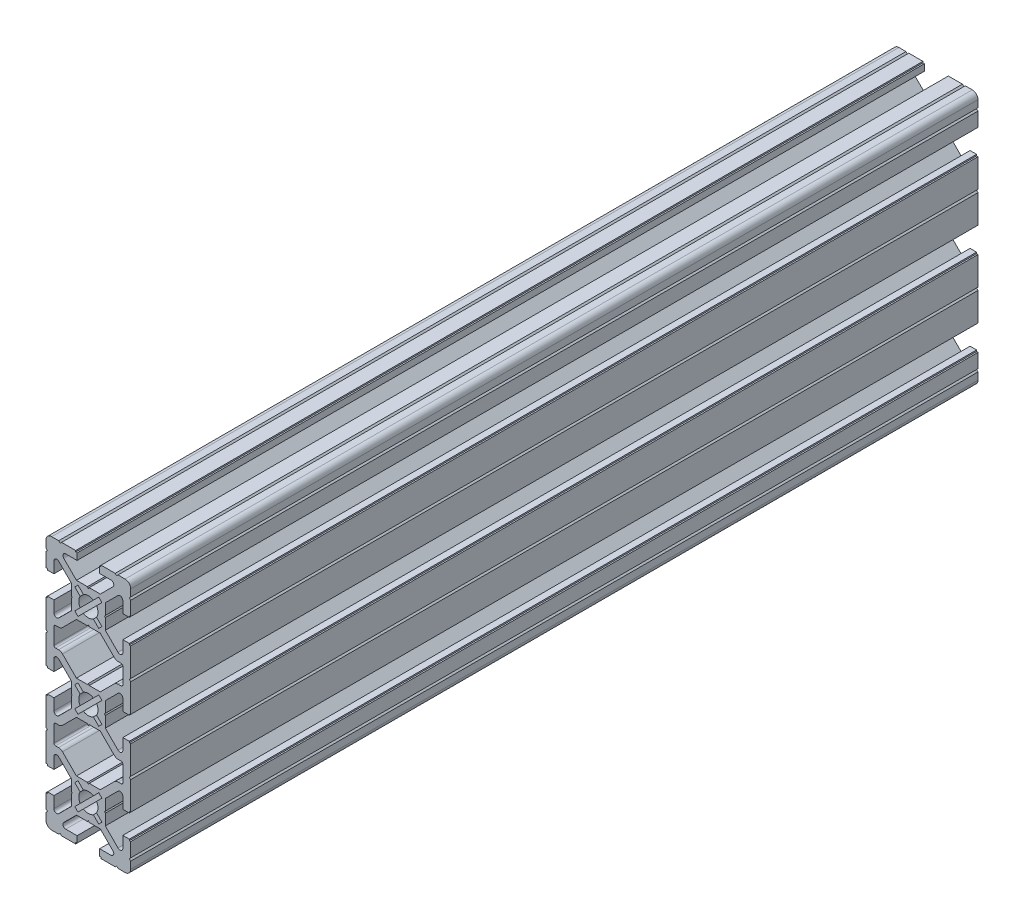
SolidWorks part; units mm, degrees
material "6063-T5"
ref_plane "Face" through (0, 0, 0) normal (0, 0, 1) x (1, 0, 0)
ref_plane "Dessus" through (0, 0, 0) normal (0, 1, 0) x (1, 0, 0)
ref_plane "Droite" through (0, 0, 0) normal (1, 0, 0) x (0, 0, -1)
other "Centre de masse"
sketch "Esquisse1" plane through (0, 0, 0) normal (0, 0, 1) x (1, 0, 0)
  line L0 (2.9023, -1.771) -> (4.8083, -3.677)
  line L1 (4.8083, -3.677) -> (3.677, -4.8083)
  line L2 (3.677, -4.8083) -> (1.771, -2.9023)
  line L3 (-1.771, -2.9023) -> (-3.677, -4.8083)
  line L4 (-3.677, -4.8083) -> (-4.8083, -3.677)
  line L5 (-4.8083, -3.677) -> (-2.9023, -1.771)
  line L6 (-2.9023, -28.229) -> (-4.8083, -26.323)
  line L7 (-4.8083, -26.323) -> (-3.677, -25.1917)
  line L8 (-3.677, -25.1917) -> (-1.771, -27.0977)
  line L9 (1.771, -27.0977) -> (3.677, -25.1917)
  line L10 (3.677, -25.1917) -> (4.8083, -26.323)
  line L11 (4.8083, -26.323) -> (2.9023, -28.229)
  line L12 (2.9023, -31.771) -> (4.8083, -33.677)
  line L13 (4.8083, -33.677) -> (3.677, -34.8083)
  line L14 (3.677, -34.8083) -> (1.771, -32.9023)
  line L15 (-1.771, -32.9023) -> (-3.677, -34.8083)
  line L16 (-3.677, -34.8083) -> (-4.8083, -33.677)
  line L17 (-4.8083, -33.677) -> (-2.9023, -31.771)
  line L18 (-9.1584, -10.9442) -> (-4.2142, -6)
  line L19 (-4.2142, -6) -> (-0.3125, -6)
  line L20 (-0.3125, -6) -> (0, -6.4691)
  line L21 (0, -6.4691) -> (0.3125, -6)
  line L22 (0.3125, -6) -> (4.2142, -6)
  line L23 (4.2142, -6) -> (9.1584, -10.9442)
  line L24 (10.5726, -11.53) -> (11.6, -11.53)
  line L25 (12.2, -12.13) -> (12.2, -17.87)
  line L26 (11.6, -18.47) -> (10.5726, -18.47)
  line L27 (9.1584, -19.0558) -> (4.2142, -24)
  line L28 (4.2142, -24) -> (0.3125, -24)
  line L29 (0.3125, -24) -> (0, -24.5)
  line L30 (0, -24.5) -> (-0.3125, -24)
  line L31 (-0.3125, -24) -> (-4.2142, -24)
  line L32 (-4.2142, -24) -> (-9.1584, -19.0558)
  line L33 (-10.5726, -18.47) -> (-11.6, -18.47)
  line L34 (-12.2, -17.87) -> (-12.2, -12.13)
  line L35 (-11.6, -11.53) -> (-10.5726, -11.53)
  line L36 (0, 54.4055) -> (0, -51.8032) construction
  line L37 (-5.7, 0) -> (-6, -0.3125)
  line L38 (-6, -0.3125) -> (-6, -4.2142)
  line L39 (-6, -4.2142) -> (-10.4929, -8.7071)
  line L40 (-12.2, -8) -> (-12.2, -4)
  line L41 (-12.2, -4) -> (-14.5, -4)
  line L42 (-14.5, -4) -> (-14.5, -4.5)
  line L43 (-14.5, -4.5) -> (-15, -4.5)
  line L44 (-15, -4.5) -> (-15, -14.5)
  line L45 (-15, -14.5) -> (-14.5, -15)
  line L46 (-14.5, -15) -> (-15, -15.5)
  line L47 (-15, -15.5) -> (-15, -25.5)
  line L48 (-15, -25.5) -> (-14.5, -25.5)
  line L49 (-14.5, -25.5) -> (-14.5, -26)
  line L50 (-14.5, -26) -> (-12.2, -26)
  line L51 (-12.2, -26) -> (-12.2, -22)
  line L52 (-10.4929, -21.2929) -> (-6, -25.7858)
  line L53 (-6, -25.7858) -> (-6, -29.6875)
  line L54 (-6, -29.6875) -> (-5.7, -30)
  line L55 (-5.7, -30) -> (-6, -30.3125)
  line L56 (-6, -30.3125) -> (-6, -34.2142)
  line L57 (-6, -34.2142) -> (-10.4929, -38.7071)
  line L58 (-12.2, -38) -> (-12.2, -34)
  line L59 (-12.2, -34) -> (-14.5, -34)
  line L60 (-14.5, -34) -> (-14.5, -34.5)
  line L61 (-14.5, -34.5) -> (-15, -34.5)
  line L62 (-15, -34.5) -> (-15, -39.5)
  line L63 (-15, -39.5) -> (-14.5, -40)
  line L64 (-14.5, -40) -> (-15, -40.5)
  line L65 (-15, -40.5) -> (-15, -43)
  line L66 (-13, -45) -> (-10.5, -45)
  line L67 (-10.5, -45) -> (-10, -44.5)
  line L68 (-10, -44.5) -> (-9.5, -45)
  line L69 (-9.5, -45) -> (-4.5, -45)
  line L70 (-4.5, -45) -> (-4.5, -44.5)
  line L71 (-4.5, -44.5) -> (-4, -44.5)
  line L72 (-4, -44.5) -> (-4, -42.2)
  line L73 (-4, -42.2) -> (-8, -42.2)
  line L74 (-8.7071, -40.4929) -> (-4.2142, -36)
  line L75 (-4.2142, -36) -> (-0.3125, -36)
  line L76 (-0.3125, -36) -> (0, -35.5)
  line L77 (0, -35.5) -> (0.3125, -36)
  line L78 (0.3125, -36) -> (4.2142, -36)
  line L79 (4.2142, -36) -> (8.7071, -40.4929)
  line L80 (8, -42.2) -> (4, -42.2)
  line L81 (4, -42.2) -> (4, -44.5)
  line L82 (4, -44.5) -> (4.5, -44.5)
  line L83 (4.5, -44.5) -> (4.5, -45)
  line L84 (4.5, -45) -> (9.5, -45)
  line L85 (9.5, -45) -> (10, -44.5)
  line L86 (10, -44.5) -> (10.5, -45)
  line L87 (10.5, -45) -> (13, -45)
  line L88 (15, -43) -> (15, -40.5)
  line L89 (15, -40.5) -> (14.5, -40)
  line L90 (14.5, -40) -> (15, -39.5)
  line L91 (15, -39.5) -> (15, -34.5)
  line L92 (15, -34.5) -> (14.5, -34.5)
  line L93 (14.5, -34.5) -> (14.5, -34)
  line L94 (14.5, -34) -> (12.2, -34)
  line L95 (12.2, -34) -> (12.2, -38)
  line L96 (10.4929, -38.7071) -> (6, -34.2142)
  line L97 (6, -34.2142) -> (6, -30.3125)
  line L98 (6, -30.3125) -> (5.7, -30)
  line L99 (5.7, -30) -> (6, -29.6875)
  line L100 (6, -29.6875) -> (6, -25.7858)
  line L101 (6, -25.7858) -> (10.4929, -21.2929)
  line L102 (12.2, -22) -> (12.2, -26)
  line L103 (12.2, -26) -> (14.5, -26)
  line L104 (14.5, -26) -> (14.5, -25.5)
  line L105 (14.5, -25.5) -> (15, -25.5)
  line L106 (15, -25.5) -> (15, -15.5)
  line L107 (15, -15.5) -> (14.5, -15)
  line L108 (14.5, -15) -> (15, -14.5)
  line L109 (15, -14.5) -> (15, -4.5)
  line L110 (15, -4.5) -> (14.5, -4.5)
  line L111 (14.5, -4.5) -> (14.5, -4)
  line L112 (14.5, -4) -> (12.2, -4)
  line L113 (12.2, -4) -> (12.2, -8)
  line L114 (10.4929, -8.7071) -> (6, -4.2142)
  line L115 (6, -4.2142) -> (6, -0.3125)
  line L116 (6, -0.3125) -> (5.7, 0)
  line L117 (-20.5652, 0) -> (29.163, 0) construction
  line L118 (-20.5652, -15) -> (29.163, -15) construction
  line L119 (-20.5652, -30) -> (29.163, -30) construction
  line L120 (6, 0.3125) -> (5.7, 0)
  line L121 (6, 4.2142) -> (6, 0.3125)
  line L122 (10.4929, 8.7071) -> (6, 4.2142)
  line L123 (12.2, 4) -> (12.2, 8)
  line L124 (14.5, 4) -> (12.2, 4)
  line L125 (14.5, 4.5) -> (14.5, 4)
  line L126 (15, 4.5) -> (14.5, 4.5)
  line L127 (15, 14.5) -> (15, 4.5)
  line L128 (14.5, 15) -> (15, 14.5)
  line L129 (15, 15.5) -> (14.5, 15)
  line L130 (15, 25.5) -> (15, 15.5)
  line L131 (14.5, 25.5) -> (15, 25.5)
  line L132 (14.5, 26) -> (14.5, 25.5)
  line L133 (12.2, 26) -> (14.5, 26)
  line L134 (12.2, 22) -> (12.2, 26)
  line L135 (6, 25.7858) -> (10.4929, 21.2929)
  line L136 (6, 29.6875) -> (6, 25.7858)
  line L137 (5.7, 30) -> (6, 29.6875)
  line L138 (6, 30.3125) -> (5.7, 30)
  line L139 (6, 34.2142) -> (6, 30.3125)
  line L140 (10.4929, 38.7071) -> (6, 34.2142)
  line L141 (12.2, 34) -> (12.2, 38)
  line L142 (14.5, 34) -> (12.2, 34)
  line L143 (14.5, 34.5) -> (14.5, 34)
  line L144 (15, 34.5) -> (14.5, 34.5)
  line L145 (15, 39.5) -> (15, 34.5)
  line L146 (14.5, 40) -> (15, 39.5)
  line L147 (15, 40.5) -> (14.5, 40)
  line L148 (15, 43) -> (15, 40.5)
  line L149 (10.5, 45) -> (13, 45)
  line L150 (10, 44.5) -> (10.5, 45)
  line L151 (9.5, 45) -> (10, 44.5)
  line L152 (4.5, 45) -> (9.5, 45)
  line L153 (4.5, 44.5) -> (4.5, 45)
  line L154 (4, 44.5) -> (4.5, 44.5)
  line L155 (4, 42.2) -> (4, 44.5)
  line L156 (8, 42.2) -> (4, 42.2)
  line L157 (4.2142, 36) -> (8.7071, 40.4929)
  line L158 (0.3125, 36) -> (4.2142, 36)
  line L159 (0, 35.5) -> (0.3125, 36)
  line L160 (-0.3125, 36) -> (0, 35.5)
  line L161 (-4.2142, 36) -> (-0.3125, 36)
  line L162 (-8.7071, 40.4929) -> (-4.2142, 36)
  line L163 (-4, 42.2) -> (-8, 42.2)
  line L164 (-4, 44.5) -> (-4, 42.2)
  line L165 (-4.5, 44.5) -> (-4, 44.5)
  line L166 (-4.5, 45) -> (-4.5, 44.5)
  line L167 (-9.5, 45) -> (-4.5, 45)
  line L168 (-10, 44.5) -> (-9.5, 45)
  line L169 (-10.5, 45) -> (-10, 44.5)
  line L170 (-13, 45) -> (-10.5, 45)
  line L171 (-15, 40.5) -> (-15, 43)
  line L172 (-14.5, 40) -> (-15, 40.5)
  line L173 (-15, 39.5) -> (-14.5, 40)
  line L174 (-15, 34.5) -> (-15, 39.5)
  line L175 (-14.5, 34.5) -> (-15, 34.5)
  line L176 (-14.5, 34) -> (-14.5, 34.5)
  line L177 (-12.2, 34) -> (-14.5, 34)
  line L178 (-12.2, 38) -> (-12.2, 34)
  line L179 (-6, 34.2142) -> (-10.4929, 38.7071)
  line L180 (-6, 30.3125) -> (-6, 34.2142)
  line L181 (-5.7, 30) -> (-6, 30.3125)
  line L182 (-6, 29.6875) -> (-5.7, 30)
  line L183 (-6, 25.7858) -> (-6, 29.6875)
  line L184 (-10.4929, 21.2929) -> (-6, 25.7858)
  line L185 (-12.2, 26) -> (-12.2, 22)
  line L186 (-14.5, 26) -> (-12.2, 26)
  line L187 (-14.5, 25.5) -> (-14.5, 26)
  line L188 (-15, 25.5) -> (-14.5, 25.5)
  line L189 (-15, 15.5) -> (-15, 25.5)
  line L190 (-14.5, 15) -> (-15, 15.5)
  line L191 (-15, 14.5) -> (-14.5, 15)
  line L192 (-15, 4.5) -> (-15, 14.5)
  line L193 (-14.5, 4.5) -> (-15, 4.5)
  line L194 (-14.5, 4) -> (-14.5, 4.5)
  line L195 (-12.2, 4) -> (-14.5, 4)
  line L196 (-12.2, 8) -> (-12.2, 4)
  line L197 (-6, 4.2142) -> (-10.4929, 8.7071)
  line L198 (-6, 0.3125) -> (-6, 4.2142)
  line L199 (-5.7, 0) -> (-6, 0.3125)
  line L200 (-11.6, 11.53) -> (-10.5726, 11.53)
  line L201 (-12.2, 17.87) -> (-12.2, 12.13)
  line L202 (-10.5726, 18.47) -> (-11.6, 18.47)
  line L203 (-4.2142, 24) -> (-9.1584, 19.0558)
  line L204 (-0.3125, 24) -> (-4.2142, 24)
  line L205 (0, 24.5) -> (-0.3125, 24)
  line L206 (0.3125, 24) -> (0, 24.5)
  line L207 (4.2142, 24) -> (0.3125, 24)
  line L208 (9.1584, 19.0558) -> (4.2142, 24)
  line L209 (11.6, 18.47) -> (10.5726, 18.47)
  line L210 (12.2, 12.13) -> (12.2, 17.87)
  line L211 (10.5726, 11.53) -> (11.6, 11.53)
  line L212 (4.2142, 6) -> (9.1584, 10.9442)
  line L213 (0.3125, 6) -> (4.2142, 6)
  line L214 (0, 6.4691) -> (0.3125, 6)
  line L215 (-0.3125, 6) -> (0, 6.4691)
  line L216 (-4.2142, 6) -> (-0.3125, 6)
  line L217 (-9.1584, 10.9442) -> (-4.2142, 6)
  line L218 (-4.8083, 33.677) -> (-2.9023, 31.771)
  line L219 (-3.677, 34.8083) -> (-4.8083, 33.677)
  line L220 (-1.771, 32.9023) -> (-3.677, 34.8083)
  line L221 (3.677, 34.8083) -> (1.771, 32.9023)
  line L222 (4.8083, 33.677) -> (3.677, 34.8083)
  line L223 (2.9023, 31.771) -> (4.8083, 33.677)
  line L224 (4.8083, 26.323) -> (2.9023, 28.229)
  line L225 (3.677, 25.1917) -> (4.8083, 26.323)
  line L226 (1.771, 27.0977) -> (3.677, 25.1917)
  line L227 (-3.677, 25.1917) -> (-1.771, 27.0977)
  line L228 (-4.8083, 26.323) -> (-3.677, 25.1917)
  line L229 (-2.9023, 28.229) -> (-4.8083, 26.323)
  line L230 (-4.8083, 3.677) -> (-2.9023, 1.771)
  line L231 (-3.677, 4.8083) -> (-4.8083, 3.677)
  line L232 (-1.771, 2.9023) -> (-3.677, 4.8083)
  line L233 (3.677, 4.8083) -> (1.771, 2.9023)
  line L234 (4.8083, 3.677) -> (3.677, 4.8083)
  line L235 (2.9023, 1.771) -> (4.8083, 3.677)
  line L236 (-20.5652, 30) -> (29.163, 30) construction
  arc A0 (12.2, 8) -> (10.4929, 8.7071) centre (11.2, 8) ccw
  arc A1 (-2.9023, 1.771) -> (-2.9023, -1.771) centre (0, 0) ccw
  arc A2 (10.4929, 21.2929) -> (12.2, 22) centre (11.2, 22) ccw
  arc A3 (-1.771, -27.0977) -> (1.771, -27.0977) centre (0, -30) cw
  arc A4 (2.9023, -28.229) -> (2.9023, -31.771) centre (0, -30) cw
  arc A5 (1.771, -32.9023) -> (-1.771, -32.9023) centre (0, -30) cw
  arc A6 (-2.9023, -31.771) -> (-2.9023, -28.229) centre (0, -30) cw
  arc A7 (9.1584, -10.9442) -> (10.5726, -11.53) centre (10.5726, -9.53) ccw
  arc A8 (11.6, -11.53) -> (12.2, -12.13) centre (11.6, -12.13) cw
  arc A9 (12.2, -17.87) -> (11.6, -18.47) centre (11.6, -17.87) cw
  arc A10 (10.5726, -18.47) -> (9.1584, -19.0558) centre (10.5726, -20.47) ccw
  arc A11 (-9.1584, -19.0558) -> (-10.5726, -18.47) centre (-10.5726, -20.47) ccw
  arc A12 (-11.6, -18.47) -> (-12.2, -17.87) centre (-11.6, -17.87) cw
  arc A13 (-12.2, -12.13) -> (-11.6, -11.53) centre (-11.6, -12.13) cw
  arc A14 (-10.5726, -11.53) -> (-9.1584, -10.9442) centre (-10.5726, -9.53) ccw
  arc A15 (-10.4929, -8.7071) -> (-12.2, -8) centre (-11.2, -8) cw
  arc A16 (-12.2, -22) -> (-10.4929, -21.2929) centre (-11.2, -22) cw
  arc A17 (-10.4929, -38.7071) -> (-12.2, -38) centre (-11.2, -38) cw
  arc A18 (-15, -43) -> (-13, -45) centre (-13, -43) ccw
  arc A19 (-8, -42.2) -> (-8.7071, -40.4929) centre (-8, -41.2) cw
  arc A20 (8.7071, -40.4929) -> (8, -42.2) centre (8, -41.2) cw
  arc A21 (13, -45) -> (15, -43) centre (13, -43) ccw
  arc A22 (12.2, -38) -> (10.4929, -38.7071) centre (11.2, -38) cw
  arc A23 (10.4929, -21.2929) -> (12.2, -22) centre (11.2, -22) cw
  arc A24 (12.2, -8) -> (10.4929, -8.7071) centre (11.2, -8) cw
  arc A25 (12.2, 38) -> (10.4929, 38.7071) centre (11.2, 38) ccw
  arc A26 (13, 45) -> (15, 43) centre (13, 43) cw
  arc A27 (8.7071, 40.4929) -> (8, 42.2) centre (8, 41.2) ccw
  arc A28 (-8, 42.2) -> (-8.7071, 40.4929) centre (-8, 41.2) ccw
  arc A29 (-15, 43) -> (-13, 45) centre (-13, 43) cw
  arc A30 (-10.4929, 38.7071) -> (-12.2, 38) centre (-11.2, 38) ccw
  arc A31 (-12.2, 22) -> (-10.4929, 21.2929) centre (-11.2, 22) ccw
  arc A32 (-10.4929, 8.7071) -> (-12.2, 8) centre (-11.2, 8) ccw
  arc A33 (-10.5726, 11.53) -> (-9.1584, 10.9442) centre (-10.5726, 9.53) cw
  arc A34 (-12.2, 12.13) -> (-11.6, 11.53) centre (-11.6, 12.13) ccw
  arc A35 (-11.6, 18.47) -> (-12.2, 17.87) centre (-11.6, 17.87) ccw
  arc A36 (-9.1584, 19.0558) -> (-10.5726, 18.47) centre (-10.5726, 20.47) cw
  arc A37 (10.5726, 18.47) -> (9.1584, 19.0558) centre (10.5726, 20.47) cw
  arc A38 (12.2, 17.87) -> (11.6, 18.47) centre (11.6, 17.87) ccw
  arc A39 (11.6, 11.53) -> (12.2, 12.13) centre (11.6, 12.13) ccw
  arc A40 (9.1584, 10.9442) -> (10.5726, 11.53) centre (10.5726, 9.53) cw
  arc A41 (-2.9023, 31.771) -> (-2.9023, 28.229) centre (0, 30) ccw
  arc A42 (1.771, 32.9023) -> (-1.771, 32.9023) centre (0, 30) ccw
  arc A43 (2.9023, 28.229) -> (2.9023, 31.771) centre (0, 30) ccw
  arc A44 (-1.771, 27.0977) -> (1.771, 27.0977) centre (0, 30) ccw
  arc A45 (1.771, 2.9023) -> (-1.771, 2.9023) centre (0, 0) ccw
  arc A46 (2.9023, -1.771) -> (2.9023, 1.771) centre (0, 0) ccw
  arc A47 (-1.771, -2.9023) -> (1.771, -2.9023) centre (0, 0) ccw
  dimension "D19" = 2
  dimension "D21" = 3.4
  dimension "D22" = 3.4
  dimension "D1" = 30
  dimension "D3" = 15
  dimension "D4" = 15
  dimension "D5" = 22
  dimension "D6" = 12.2
  dimension "D7" = 4
  dimension "D8" = 4.5
  dimension "D9" = 15
  dimension "D10" = 12.2
  dimension "D11" = 8
  dimension "D12" = 9
  dimension "D13" = 11
  dimension "D14" = 10.5
  dimension "D15" = 0.5
  dimension "D16" = 9
  dimension "D17" = 9
  dimension "D18" = 9
  dimension "D20" = 6
  dimension "D23" = 90
  dimension "D25" = 6
extrude "Boss.-Extru.1" add sketch "Esquisse1" along normal blind 300
